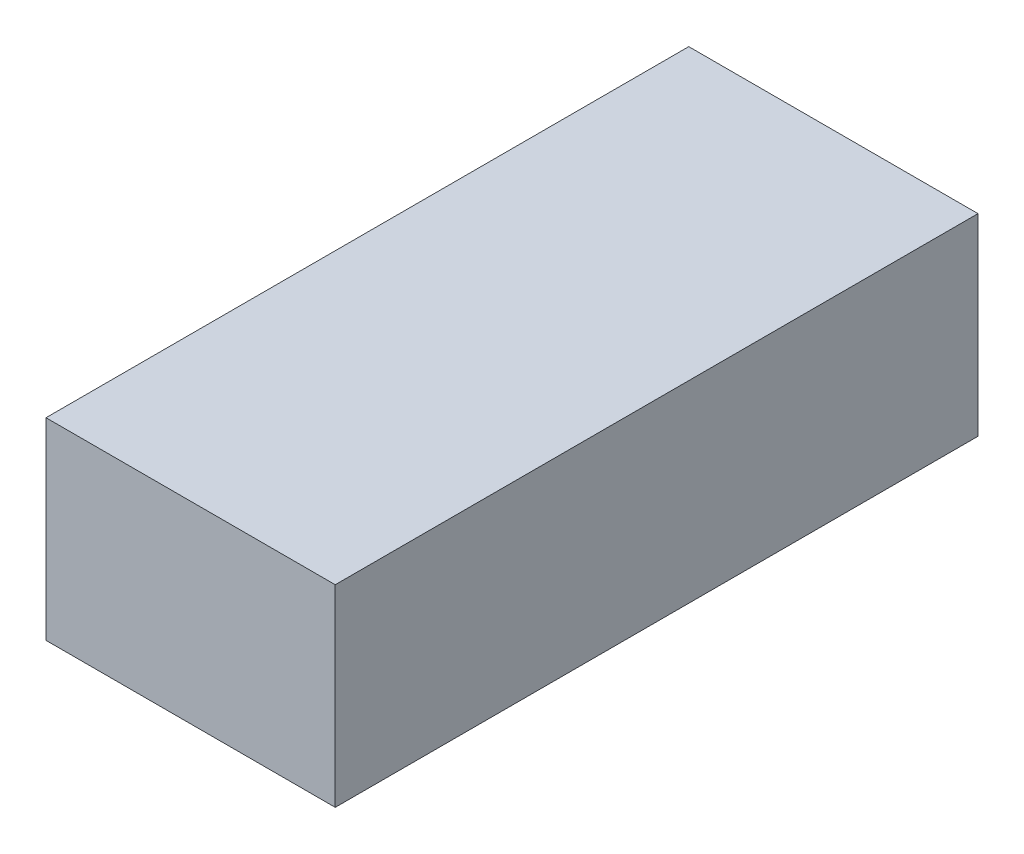
SolidWorks part; units mm, degrees
ref_plane "Front Plane" through (0, 0, 0) normal (0, 0, 1) x (1, 0, 0)
ref_plane "Top Plane" through (0, 0, 0) normal (0, 1, 0) x (1, 0, 0)
ref_plane "Right Plane" through (0, 0, 0) normal (1, 0, 0) x (0, 0, -1)
sketch "Sketch1" plane through (0, 0, 0) normal (0, 1, 0) x (1, 0, 0)
  line L1 (2.25, 5) -> (-2.25, 5)
  line L2 (2.25, 5) -> (2.25, -5)
  line L3 (2.25, -5) -> (-2.25, -5)
  line L4 (-2.25, 5) -> (-2.25, -5)
  line L5 (2.25, 5) -> (-2.25, -5) construction
  line L6 (2.25, -5) -> (-2.25, 5) construction
  point P0 (0, 0)
  dimension "D1" = 4.5
  dimension "D2" = 10
extrude "Boss-Extrude1" add sketch "Sketch1" along normal blind 3
